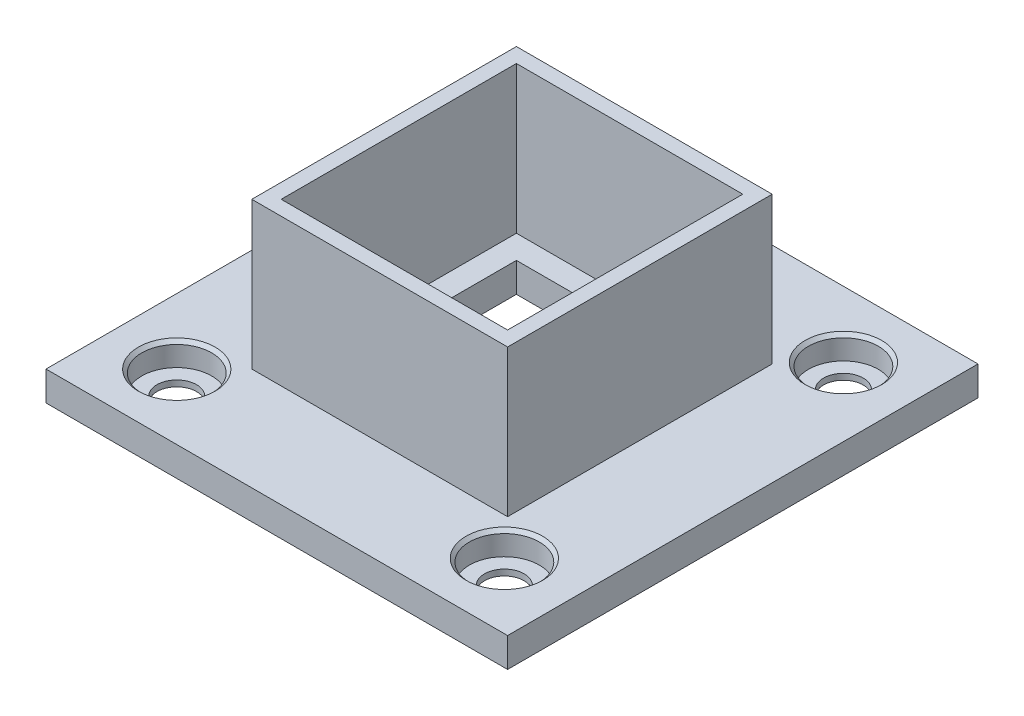
SolidWorks part; units mm, degrees
material "AISI 1020"
ref_plane "Front Plane" through (0, 0, 0) normal (0, 0, 1) x (1, 0, 0)
ref_plane "Top Plane" through (0, 0, 0) normal (0, 1, 0) x (1, 0, 0)
ref_plane "Right Plane" through (0, 0, 0) normal (1, 0, 0) x (0, 0, -1)
sketch "Sketch1" plane through (0, 0, 0) normal (0, 1, 0) x (1, 0, 0)
  line L1 (-80.1469, 69.7168) -> (76.8531, 69.7168)
  line L2 (-80.1469, 69.7168) -> (-80.1469, -90.2832)
  line L3 (-80.1469, -90.2832) -> (76.8531, -90.2832)
  line L4 (76.8531, 69.7168) -> (76.8531, -90.2832)
  dimension "D1" = 157
  dimension "D2" = 160
extrude "Boss-Extrude1" add sketch "Sketch1" along normal blind 10
sketch "Sketch2" plane through (0, 10, 0) normal (0, 1, 0) x (1, 0, 0)
  line L0 (76.8531, 69.7168) -> (-80.1469, 69.7168) construction
  line L1 (-32.1469, 21.7168) -> (28.8531, 21.7168)
  line L2 (-32.1469, 21.7168) -> (-32.1469, -42.2832)
  line L3 (-32.1469, -42.2832) -> (28.8531, -42.2832)
  line L4 (28.8531, 21.7168) -> (28.8531, -42.2832)
  line L5 (76.8531, -90.2832) -> (76.8531, 69.7168) construction
  line L6 (-80.1469, 69.7168) -> (-80.1469, -90.2832) construction
  line L7 (-80.1469, -90.2832) -> (76.8531, -90.2832) construction
  dimension "D1" = 48
  dimension "D2" = 48
  dimension "D3" = 48
  dimension "D4" = 48
extrude "Cut-Extrude1" cut sketch "Sketch2" against normal blind 10
hole_wizard "CBORE SLOT for M12 Hex Head Bolt1" positions "Sketch6" profile "Sketch4" size "M12" standard "ANSI Metric" slot yes
sketch "Sketch6" plane through (0, 10, 0) normal (0, 1, 0) x (1, 0, 0)
  point P0 (-57.8778, 47.2494)
  point P2 (53.5428, 47.2494)
  point P4 (53.5428, -68.0762)
  point P6 (-57.8778, -68.0762)
sketch "Sketch4" plane through (-57.8778, 10, -47.2494) normal (1, 0, 0) x (0, 0, 1)
  line L0 (0, 0) -> (0, 22.0558)
  line L1 (0, 22.0558) -> (6.75, 18)
  line L2 (6.75, 18) -> (6.75, 7.95)
  line L3 (6.75, 7.95) -> (11.89, 7.95)
  line L5 (11.89, 7.95) -> (11.89, 1.135)
  line L6 (11.89, 1.135) -> (13.025, 0)
  line L7 (13.025, 0) -> (0, 0)
  line L8 (-11.89, 1.135) -> (-13.025, 0) construction
  line L10 (0, 22.0558) -> (-6.75, 18) construction
  line L11 (0, -6.35) -> (0, 107.95) construction
  dimension "Hole Dia." = 13.5
  dimension "Hole Depth" = 18
  dimension "C'Bore Dia." = 23.78
  dimension "C'Bore Depth" = 7.95
  dimension "Near C'Sink Dia." = 26.05
  dimension "Near C'Sink Angle" = 90
  dimension "Drill Angle" = 118
sketch "Sketch7" plane through (0, 10, 0) normal (0, 1, 0) x (1, 0, 0)
  line L0 (28.8531, 21.7168) -> (-32.1469, 21.7168) construction
  line L5 (-40.1469, 29.7168) -> (36.8531, 29.7168)
  line L6 (-40.1469, 29.7168) -> (-40.1469, -50.2832)
  line L7 (-40.1469, -50.2832) -> (36.8531, -50.2832)
  line L8 (36.8531, 29.7168) -> (36.8531, -50.2832)
  line L9 (28.8531, -42.2832) -> (28.8531, 21.7168) construction
  line L10 (-32.1469, -42.2832) -> (28.8531, -42.2832) construction
  line L11 (-32.1469, 21.7168) -> (-32.1469, -42.2832) construction
  dimension "D1" = 8
  dimension "D2" = 8
  dimension "D3" = 8
  dimension "D4" = 8
extrude "Extrude-Thin1" add sketch "Sketch7" along normal blind 50 thin contours L8 L7 L6 L5 thin type one direction wall 5
